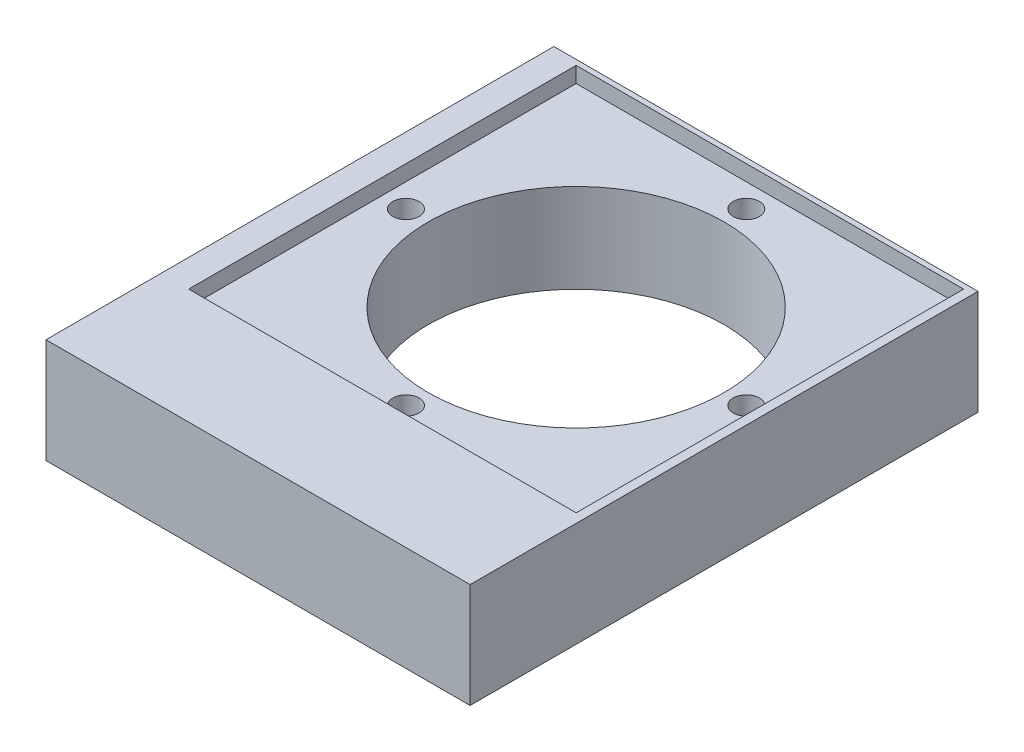
SolidWorks part; units mm, degrees
ref_plane "Front Plane" through (0, 0, 0) normal (0, 0, 1) x (1, 0, 0)
ref_plane "Top Plane" through (0, 0, 0) normal (0, 1, 0) x (1, 0, 0)
ref_plane "Right Plane" through (0, 0, 0) normal (1, 0, 0) x (0, 0, -1)
sketch "Sketch1" plane through (0, 0, 0) normal (0, 1, 0) x (1, 0, 0)
  line L1 (-40.5, 48.5) -> (40.5, 48.5)
  line L2 (-40.5, 48.5) -> (-40.5, -48.5)
  line L3 (-40.5, -48.5) -> (40.5, -48.5)
  line L4 (40.5, 48.5) -> (40.5, -48.5)
  line L5 (-40.5, 48.5) -> (40.5, -48.5) construction
  line L6 (-40.5, -48.5) -> (40.5, 48.5) construction
  point P0 (0, 0)
  dimension "D1" = 97
  dimension "D2" = 81
extrude "Boss-Extrude1" add sketch "Sketch1" along normal blind 20
sketch "Sketch2" plane through (0, 20, 0) normal (0, 1, 0) x (1, 0, 0)
  line L1 (40.5, -48.5) -> (40.5, 48.5) construction
  line L2 (40.5, 48.5) -> (-40.5, 48.5) construction
  line L7 (-26.4439, 38.6939) -> (30, -17.75) construction
  line L8 (-26.5, -17.75) -> (29.9397, 38.6897) construction
  circle A1 centre (1.75, 10.5) radius 28.25
  dimension "D2" = 38.75
  dimension "D4" = 56.5
  dimension "D3" = 38
extrude "Cut-Extrude2" cut sketch "Sketch2" against normal through all contours A1
sketch "Sketch5" plane through (0, 20, 0) normal (0, 1, 0) x (1, 0, 0)
  line L1 (-35.25, 47.5) -> (38.75, 47.5)
  line L2 (-35.25, 47.5) -> (-35.25, -26.5)
  line L3 (-35.25, -26.5) -> (38.75, -26.5)
  line L4 (38.75, 47.5) -> (38.75, -26.5)
  line L5 (-35.25, 47.5) -> (38.75, -26.5) construction
  line L6 (-35.25, -26.5) -> (38.75, 47.5) construction
  dimension "D2" = 74
  dimension "D3" = 74
extrude "Cut-Extrude3" cut sketch "Sketch5" against normal blind 3
sketch "Sketch6" plane through (0, 17, 0) normal (0, 1, 0) x (1, 0, 0)
  line L0 (-47.9199, 10.5) -> (51.4199, 10.5)
  line L1 (1.75, 64.0547) -> (1.75, -43.0547)
  circle A1 centre (-30.75, 10.5) radius 2.5
  circle A2 centre (1.75, -22) radius 2.5
  circle A3 centre (34.25, 10.5) radius 2.5
  circle A4 centre (1.75, 43) radius 2.5
  point P6 (1.75, 10.5)
  point P9 (1.75, 10.5)
  dimension "D2" = 5
  dimension "D3" = 5
  dimension "D4" = 5
  dimension "D5" = 5
extrude "Cut-Extrude4" cut sketch "Sketch6" against normal through all contours A3 | A4 | A1 | A2
